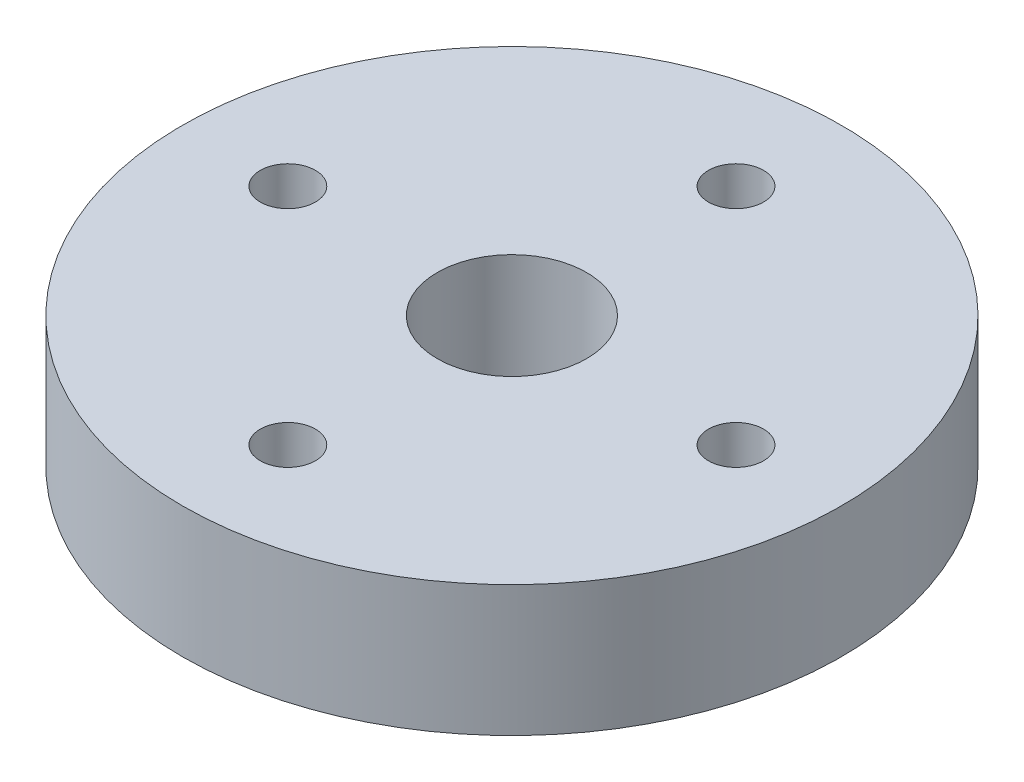
SolidWorks part; units mm, degrees
ref_plane "Front Plane" through (0, 0, 0) normal (0, 0, 1) x (1, 0, 0)
ref_plane "Top Plane" through (0, 0, 0) normal (0, 1, 0) x (1, 0, 0)
ref_plane "Right Plane" through (0, 0, 0) normal (1, 0, 0) x (0, 0, -1)
sketch "Sketch1" plane through (0, 0, 0) normal (0, 1, 0) x (1, 0, 0)
  line L0 (0, 17.65) -> (0, -17.65) construction
  line L1 (-17.65, 0) -> (17.65, 0) construction
  circle A0 centre (0, 0) radius 17.65
  circle A1 centre (0, 0) radius 4
  circle A2 centre (0, 12) radius 1.475
  circle A3 centre (-12, 0) radius 1.475
  circle A4 centre (12, 0) radius 1.475
  circle A5 centre (0, -12) radius 1.475
  dimension "D1" = 35.3
  dimension "D2" = 8
  dimension "D4" = 2.95
  dimension "D3" = 12
  dimension "D5" = 12
extrude "Boss-Extrude1" add sketch "Sketch1" along normal blind 7
